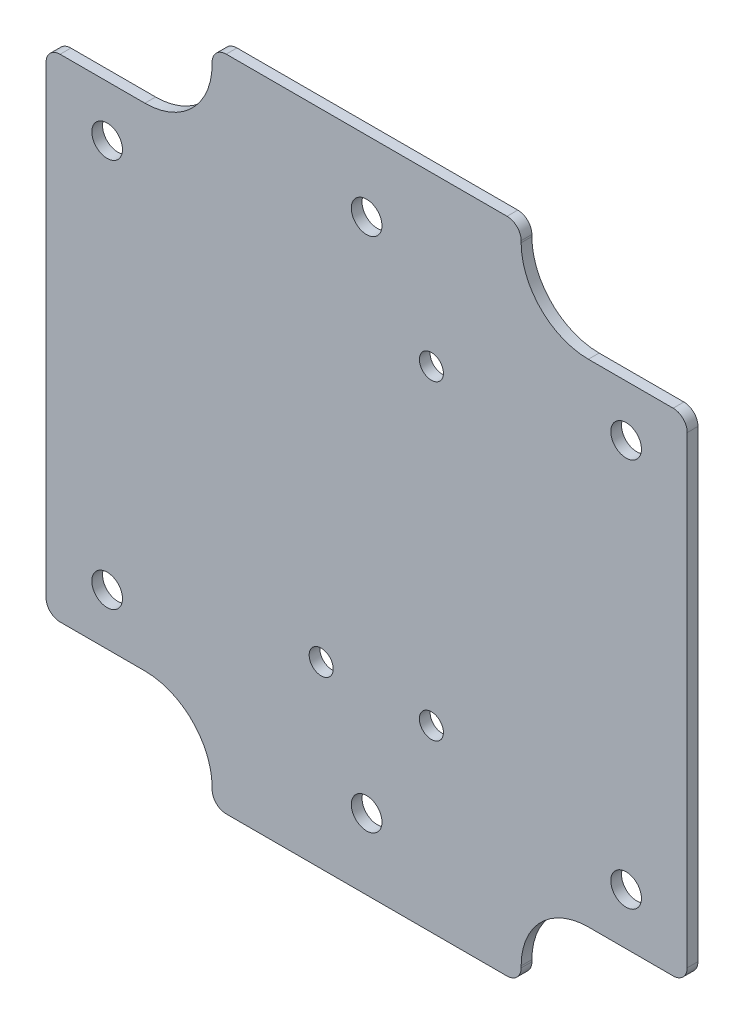
SolidWorks part; units mm, degrees
ref_plane "Front Plane" through (0, 0, 0) normal (0, 0, 1) x (1, 0, 0)
ref_plane "Top Plane" through (0, 0, 0) normal (0, 1, 0) x (1, 0, 0)
ref_plane "Right Plane" through (0, 0, 0) normal (1, 0, 0) x (0, 0, -1)
sketch "Sketch1" plane through (0, 0, 0) normal (0, 0, 1) x (1, 0, 0)
  line L0 (71.6788, 0) -> (0, 0) construction
  line L5 (35.8394, -36.7792) -> (35.8394, 0) construction
  line L6 (71.6788, -27.4828) -> (71.6788, 27.4828)
  line L7 (71.6788, -27.4828) -> (53.1114, -27.4828)
  line L8 (53.1114, -27.4828) -> (53.1114, -36.7792)
  line L9 (53.1114, -36.7792) -> (18.5674, -36.7792)
  line L10 (18.5674, -36.7792) -> (18.5674, -27.4828)
  line L11 (18.5674, -27.4828) -> (0, -27.4828)
  line L12 (0, -27.4828) -> (0, 27.4828)
  line L13 (18.5674, 27.4828) -> (0, 27.4828)
  line L14 (18.5674, 36.7792) -> (18.5674, 27.4828)
  line L15 (53.1114, 36.7792) -> (18.5674, 36.7792)
  line L16 (53.1114, 27.4828) -> (53.1114, 36.7792)
  line L17 (71.6788, 27.4828) -> (53.1114, 27.4828)
  circle A4 centre (64.8462, -21.7424) radius 1.7145
  circle A5 centre (6.8326, -21.7424) radius 1.7145
  circle A6 centre (6.8326, 21.7424) radius 1.7145
  circle A7 centre (64.8462, 21.7424) radius 1.7145
  circle A8 centre (35.8394, -28.8671) radius 1.7145
  circle A9 centre (35.8394, 28.8671) radius 1.7145
  dimension "D5" = 3.429
  dimension "D8" = 3.429
  dimension "D1" = 71.6788
  dimension "D2" = 34.544
  dimension "D3" = 9.2964
  dimension "D4" = 36.7792
  dimension "D6" = 21.7424
  dimension "D7" = 29.0068
  dimension "D9" = 28.8671
extrude "MainBody" add sketch "Sketch1" along normal blind 1.2
fillet "LargeRounds" radius 7.5184 4 edges at (53.1114, -27.4828, 0.6) (18.5674, -27.4828, 0.6) (53.1114, 27.4828, 0.6) (18.5674, 27.4828, 0.6)
fillet "SmallRounds" radius 1.5748 8 edges at (18.5674, -36.7792, 0.6) (53.1114, -36.7792, 0.6) (71.6788, -27.4828, 0.6) (71.6788, 27.4828, 0.6) (53.1114, 36.7792, 0.6) (18.5674, 36.7792, 0.6) (0, 27.4828, 0.6) (0, -27.4828, 0.6)
sketch "Sketch2" plane through (0, 0, 1.2) normal (0, 0, 1) x (1, 0, 0)
  line L0 (35.8394, -36.7792) -> (35.8394, 36.7792) construction
  line L1 (20.1422, -36.7792) -> (51.5366, -36.7792) construction
  line L2 (51.5366, 36.7792) -> (20.1422, 36.7792) construction
  line L3 (0, 0) -> (71.6788, 0) construction
  line L4 (0, 25.908) -> (0, -25.908) construction
  line L5 (71.6788, -25.908) -> (71.6788, 25.908) construction
  line L6 (30.7594, -16.76) -> (43.0794, -16.76) construction
  line L7 (43.0794, -16.76) -> (43.0794, 18.02) construction
  circle A0 centre (30.7594, -16.76) radius 1.345
  circle A1 centre (43.0794, -16.76) radius 1.345
  circle A2 centre (43.0794, 18.02) radius 1.345
  dimension "D1" = 2.69
  dimension "D3" = 2.69
  dimension "D6" = 2.69
  dimension "D2" = 5.08
  dimension "D4" = 12.32
  dimension "D5" = 16.76
  dimension "D7" = 34.78
extrude "PCBMountHoles" cut sketch "Sketch2" against normal up to next
